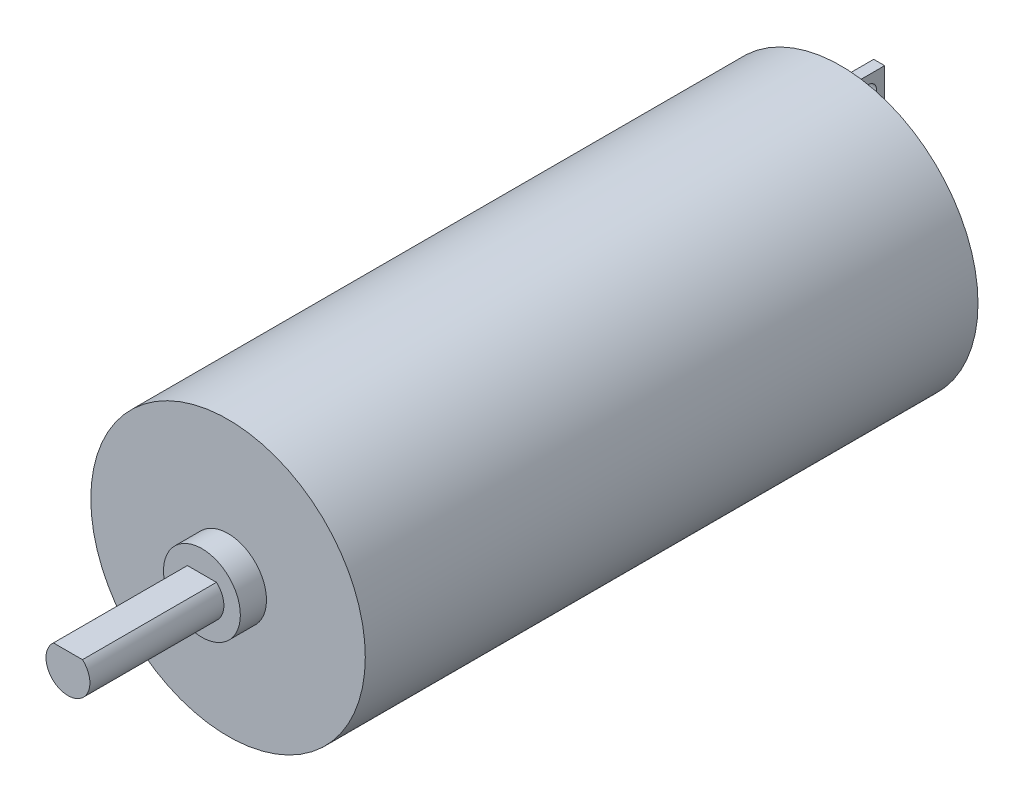
SolidWorks part; units mm, degrees
ref_plane "Front Plane" through (0, 0, 0) normal (0, 0, 1) x (1, 0, 0)
ref_plane "Top Plane" through (0, 0, 0) normal (0, 1, 0) x (1, 0, 0)
ref_plane "Right Plane" through (0, 0, 0) normal (1, 0, 0) x (0, 0, -1)
sketch "Sketch1" plane through (0, 0, 0) normal (0, 0, 1) x (1, 0, 0)
  circle A0 centre (0, 0) radius 12.5
  dimension "D1" = 25
extrude "Boss-Extrude1" add sketch "Sketch1" along normal blind 55.8
sketch "Sketch2" plane through (0, 0, 0) normal (0, 0, 1) x (1, 0, 0)
  circle A0 centre (0, 0) radius 3.5
  dimension "D1" = 7
extrude "Boss-Extrude2" add sketch "Sketch2" along normal blind 2.38 from surface at 55.8 starting at face at (12.5, 0, 55.8)
sketch "Sketch3" plane through (0, 0, 0) normal (0, 0, 1) x (1, 0, 0)
  circle A0 centre (0, 0) radius 2
  dimension "D1" = 4
extrude "Boss-Extrude3" add sketch "Sketch3" along normal blind 12.2 from surface at 58.18 starting at face at (3.5, 0, 58.18)
sketch "Sketch5" plane through (0, 0, 58.18) normal (0, 0, 1) x (1, 0, 0)
  line L1 (-1.3229, 1.5) -> (1.3229, 1.5)
  line L2 (-1.3229, 1.5) -> (-1.3229, 2.6971)
  line L3 (-1.3229, 2.6971) -> (1.3229, 2.6971)
  line L4 (1.3229, 1.5) -> (1.3229, 2.6971)
  circle A0 centre (0, 0) radius 2 construction
  circle A1 centre (0, 0) radius 2 construction
  point P8 (0, 0)
  point P9 (0, 0)
  dimension "D1" = 1.5
  dimension "D2" = 1.1971
extrude "Cut-Extrude1" cut sketch "Sketch5" along normal blind 12.2
sketch "Sketch6" plane through (0, 0, 0) normal (0, 0, 1) x (1, 0, 0)
  line L0 (13.75, 0) -> (-13.75, 0) construction
  line L1 (-0.5, 11) -> (0.5, 11)
  line L2 (-0.5, 11) -> (-0.5, 8)
  line L3 (-0.5, 8) -> (0.5, 8)
  line L4 (0.5, 11) -> (0.5, 8)
  line L5 (-0.5, -8) -> (0.5, -8)
  line L6 (-0.5, -8) -> (-0.5, -11)
  line L7 (-0.5, -11) -> (0.5, -11)
  line L8 (0.5, -8) -> (0.5, -11)
  line L9 (0, -13.75) -> (0, 13.75) construction
  dimension "D1" = 3
  dimension "D2" = 3
  dimension "D3" = 11
  dimension "D4" = 11
  dimension "D5" = 1
  dimension "D6" = 1
  dimension "D7" = 0.5
  dimension "D8" = 0.5
extrude "Boss-Extrude4" add sketch "Sketch6" against normal blind 3.5
sketch "Sketch7" plane through (0, 0, 0) normal (1, 0, 0) x (0, 0, -1)
  line L0 (0, 13.75) -> (0, -13.75) construction
  line L1 (3.5, -11) -> (0, -11) construction
  line L2 (3.5, 8) -> (0, 8) construction
  circle A0 centre (2, 9.5) radius 0.75
  circle A1 centre (2, -9.5) radius 0.75
  dimension "D5" = 1.5
  dimension "D6" = 1.5
  dimension "D1" = 2
  dimension "D2" = 2
  dimension "D3" = 1.5
  dimension "D4" = 1.5
extrude "Cut-Extrude2" cut sketch "Sketch7" against normal through all both and the other way through all
